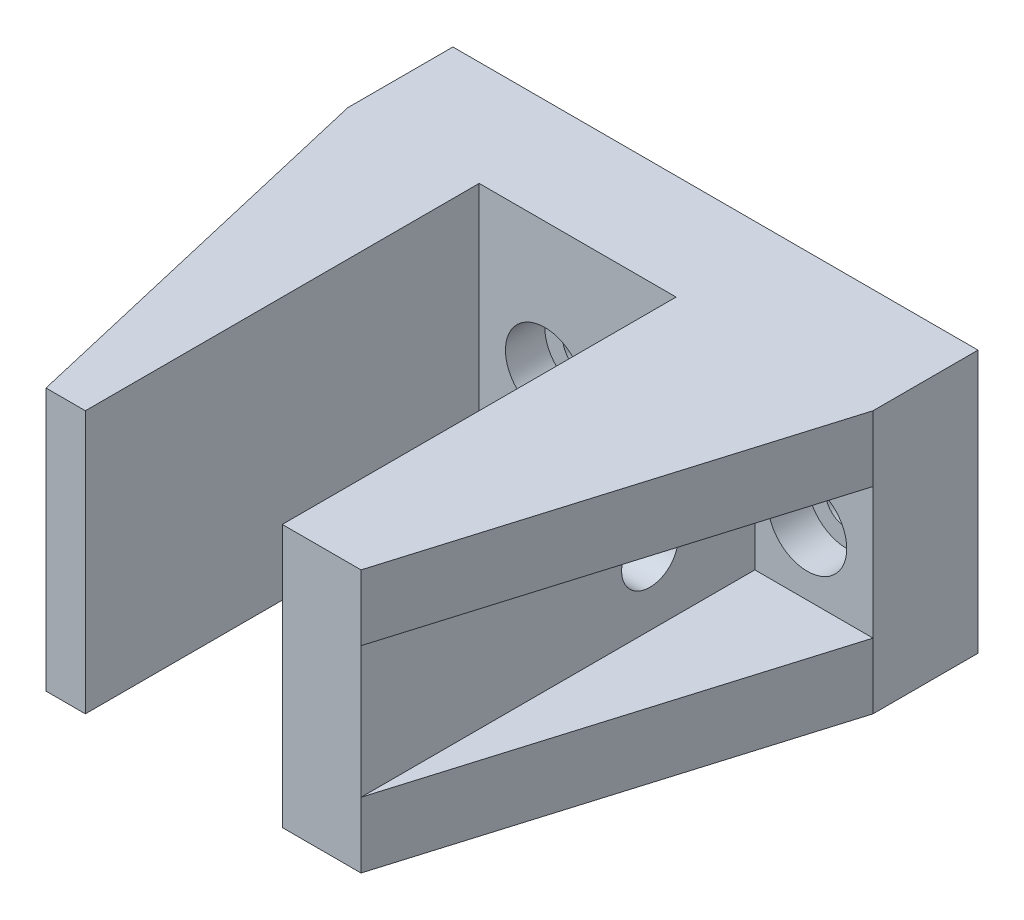
SolidWorks part; units mm, degrees
ref_plane "Front Plane" through (0, 0, 0) normal (0, 0, 1) x (1, 0, 0)
ref_plane "Top Plane" through (0, 0, 0) normal (0, 1, 0) x (1, 0, 0)
ref_plane "Right Plane" through (0, 0, 0) normal (1, 0, 0) x (0, 0, -1)
sketch "Sketch1" plane through (0, 0, 0) normal (0, 0, 1) x (1, 0, 0)
  line L1 (20, -10) -> (-20, -10)
  line L2 (20, -10) -> (20, 10)
  line L3 (20, 10) -> (-20, 10)
  line L4 (-20, -10) -> (-20, 10)
  line L5 (20, -10) -> (-20, 10) construction
  line L6 (20, 10) -> (-20, -10) construction
  circle A0 centre (-5, 0) radius 1.65
  circle A1 centre (14.9998, -0.0942) radius 1.65
  point P0 (0, 0)
  dimension "D4" = 3.3
  dimension "D5" = 15
  dimension "D6" = 10
  dimension "D1" = 20
  dimension "D2" = 40
  dimension "D3" = 20
extrude "Boss-Extrude1" add sketch "Sketch1" along normal blind 8
sketch "Sketch3" plane through (0, 0, 8) normal (0, 0, 1) x (1, 0, 0)
  line L0 (20, 10) -> (-20, 10) construction
  line L1 (-13, -10) -> (-10, -10)
  line L2 (-13, -10) -> (-13, 10)
  line L3 (-13, 10) -> (-10, 10)
  line L4 (-10, -10) -> (-10, 10)
  line L5 (-13, -10) -> (-10, 10) construction
  line L6 (-13, 10) -> (-10, -10) construction
  line L7 (-20, -10) -> (20, -10) construction
  line L8 (5, -10) -> (11, -10)
  line L9 (5, -10) -> (5, 10)
  line L10 (5, 10) -> (11, 10)
  line L11 (11, -10) -> (11, 10)
  line L12 (5, -10) -> (11, 10) construction
  line L13 (5, 10) -> (11, -10) construction
  point P0 (-11.5, 0)
  point P7 (8, 0)
  dimension "D1" = 3
  dimension "D2" = 6
  dimension "D3" = 15
  dimension "D4" = 10
extrude "Boss-Extrude2" add sketch "Sketch3" along normal blind 30
sketch "Sketch5" plane through (0, 10, 0) normal (0, 1, 0) x (1, 0, 0)
  line L0 (-20, -8) -> (-13, -38)
  line L1 (-13, -38) -> (-13, -8)
  line L2 (-13, -8) -> (-20, -8)
  line L3 (20, -8) -> (11, -8)
  line L4 (11, -8) -> (11, -38)
  line L5 (11, -38) -> (20, -8)
extrude "Boss-Extrude3" add sketch "Sketch5" against normal up to surface (20 mm away) up to face at (-1.1667, -10, 16.6667)
sketch "Sketch6" plane through (0, 0, 38) normal (0, 0, 1) x (1, 0, 0)
  line L0 (-13, 10) -> (-13, -10) construction
  line L1 (-13, 5) -> (-20, 5)
  line L2 (-13, 5) -> (-13, -5)
  line L3 (-13, -5) -> (-20, -5)
  line L4 (-20, 5) -> (-20, -5)
  line L5 (-20, 10) -> (-20, -10) construction
  line L6 (11, -10) -> (11, 10) construction
  line L7 (11, 5) -> (20, 5)
  line L8 (11, 5) -> (11, -5)
  line L9 (11, -5) -> (20, -5)
  line L10 (20, 5) -> (20, -5)
  line L11 (20, -10) -> (20, 10) construction
  line L12 (-20, 10) -> (-13, 10) construction
  line L13 (11, 10) -> (20, 10) construction
  dimension "D1" = 5
  dimension "D2" = 10
  dimension "D3" = 5
extrude "Cut-Extrude2" cut sketch "Sketch6" against normal up to surface (30 mm away) up to face at (-3.35, 0, 8)
sketch "Sketch7" plane through (11, 0, 0) normal (1, 0, 0) x (0, 0, -1)
  line L0 (-38, 5) -> (-38, -5) construction
  line L1 (-8, 5) -> (-38, 5) construction
  circle A0 centre (-16, 0) radius 2.15
  dimension "D1" = 4.3
  dimension "D2" = 22
  dimension "D3" = 5
extrude "Cut-Extrude3" cut sketch "Sketch7" against normal up to surface (6 mm away) up to face at (5, 0, 23)
sketch "Sketch8" plane through (5, 0, 0) normal (-1, 0, 0) x (0, 0, 1)
  line L0 (38, 10) -> (38, -10) construction
  line L1 (19.55, 2.0496) -> (16, 4.0992)
  line L2 (16, 4.0992) -> (12.45, 2.0496)
  line L3 (12.45, 2.0496) -> (12.45, -2.0496)
  line L4 (12.45, -2.0496) -> (16, -4.0992)
  line L5 (16, -4.0992) -> (19.55, -2.0496)
  line L6 (19.55, -2.0496) -> (19.55, 2.0496)
  line L7 (21.55, 3.2043) -> (16, 6.4086)
  line L8 (16, 6.4086) -> (10.45, 3.2043)
  line L9 (10.45, 3.2043) -> (10.45, -3.2043)
  line L10 (10.45, -3.2043) -> (16, -6.4086)
  line L11 (16, -6.4086) -> (21.55, -3.2043)
  line L12 (21.55, -3.2043) -> (21.55, 3.2043)
  circle A0 centre (16, 0) radius 3.55 construction
  circle A1 centre (16, 0) radius 5.55 construction
  dimension "D1" = 7.1
  dimension "D2" = 2
extrude "Cut-Extrude4" cut sketch "Sketch8" against normal blind 2.5 contours L1 L2 L3 L4 L5 L6
sketch "Sketch10" plane through (0, 0, 8) normal (0, 0, 1) x (1, 0, 0)
  circle A0 centre (-5, 0) radius 3
  circle A1 centre (14.9998, -0.0942) radius 3
  dimension "D1" = 6
extrude "Cut-Extrude5" cut sketch "Sketch10" against normal blind 3 contours A0 | A1
